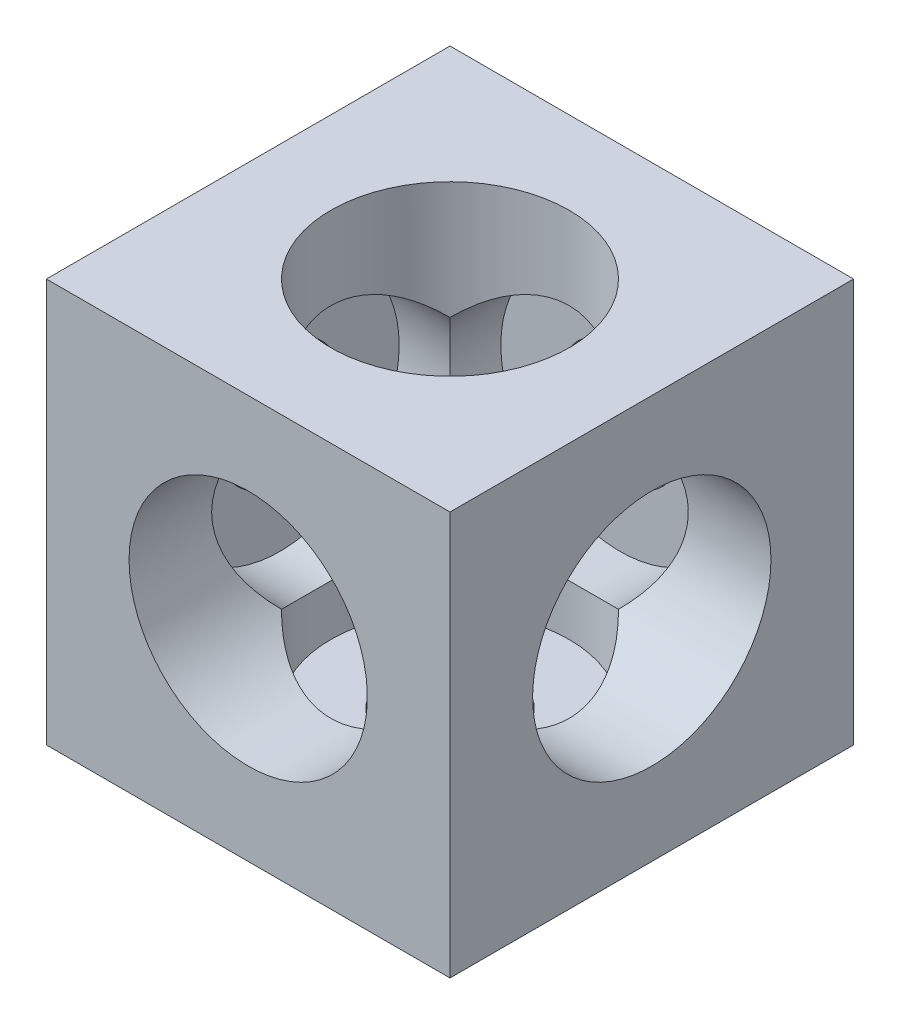
SolidWorks part; units mm, degrees
ref_plane "Front Plane" through (0, 0, 0) normal (0, 0, 1) x (1, 0, 0)
ref_plane "Top Plane" through (0, 0, 0) normal (0, 1, 0) x (1, 0, 0)
ref_plane "Right Plane" through (0, 0, 0) normal (1, 0, 0) x (0, 0, -1)
sketch "Sketch1" plane through (0, 0, 0) normal (0, 0, 1) x (1, 0, 0)
  line L1 (0, 0) -> (25.4, 0)
  line L2 (0, 0) -> (0, 25.4)
  line L3 (0, 25.4) -> (25.4, 25.4)
  line L4 (25.4, 0) -> (25.4, 25.4)
  dimension "D1" = 25.4
  dimension "D2" = 25.4
extrude "Boss-Extrude1" add sketch "Sketch1" along normal blind 25.4
sketch "Sketch2" plane through (0, 0, 0) normal (0, 0, -1) x (-1, 0, 0)
  circle A0 centre (-12.7, 12.7) radius 7.5
extrude "Cut-Extrude1" cut sketch "Sketch2" against normal through all from offset 2 offset against normal yes
sketch "Sketch4" plane through (0, 0, 0) normal (0, -1, 0) x (1, 0, 0)
  circle A0 centre (12.7, 12.7) radius 7.5
extrude "Cut-Extrude3" cut sketch "Sketch4" against normal through all from offset 2 offset against normal yes
sketch "Sketch5" plane through (0, 2, 0) normal (0, 1, 0) x (1, 0, 0)
  circle A0 centre (12.7, -12.7) radius 3.75
extrude "Cut-Extrude4" cut sketch "Sketch5" against normal through all
sketch "Sketch7" plane through (0, 0, 2) normal (0, 0, 1) x (1, 0, 0)
  circle A0 centre (12.7, 12.7) radius 3.75
extrude "Cut-Extrude6" cut sketch "Sketch7" against normal through all
sketch "Sketch6" plane through (0, 0, 0) normal (-1, 0, 0) x (0, 0, 1)
  circle A0 centre (12.7, 12.7) radius 3.75
extrude "Cut-Extrude7" cut sketch "Sketch6" against normal blind 10
sketch "Sketch3" plane through (0, 0, 0) normal (1, 0, 0) x (0, 0, -1)
  circle A0 centre (-12.7, 12.7) radius 7.5
extrude "Cut-Extrude8" cut sketch "Sketch3" along normal through all from offset 2
